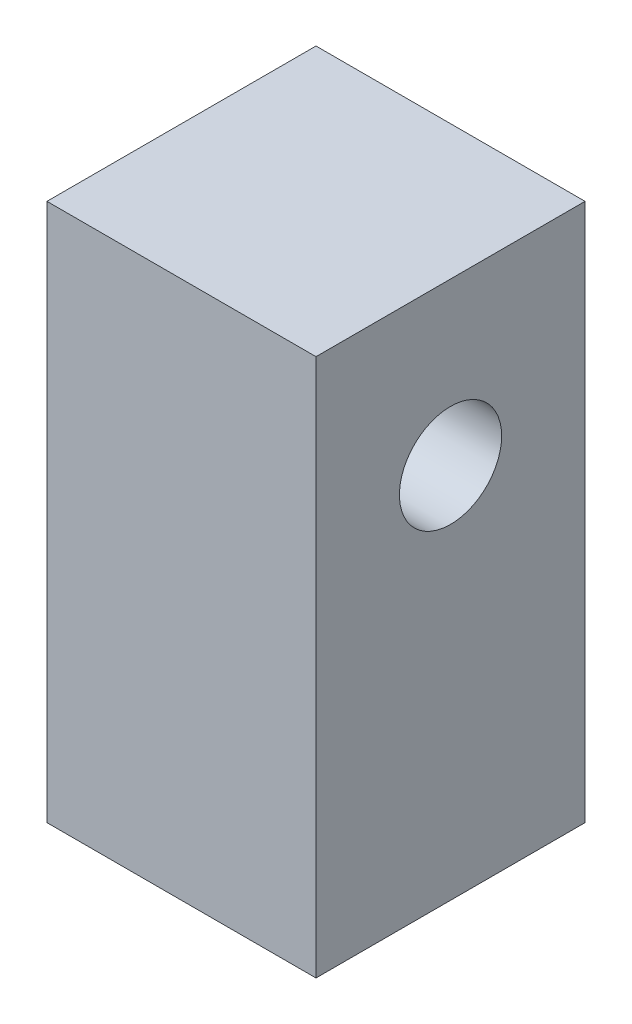
SolidWorks part; units mm, degrees
material "6061 Alloy"
ref_plane "Front Plane" through (0, 0, 0) normal (0, 0, 1) x (1, 0, 0)
ref_plane "Top Plane" through (0, 0, 0) normal (0, 1, 0) x (1, 0, 0)
ref_plane "Right Plane" through (0, 0, 0) normal (1, 0, 0) x (0, 0, -1)
sketch "Croquis1" plane through (0, 0, 0) normal (0, 1, 0) x (1, 0, 0)
  line L1 (6.35, -6.35) -> (-6.35, -6.35)
  line L2 (6.35, -6.35) -> (6.35, 6.35)
  line L3 (6.35, 6.35) -> (-6.35, 6.35)
  line L4 (-6.35, -6.35) -> (-6.35, 6.35)
  line L5 (6.35, -6.35) -> (-6.35, 6.35) construction
  line L6 (6.35, 6.35) -> (-6.35, -6.35) construction
  point P0 (0, 0)
  dimension "D1" = 12.7
  dimension "D2" = 12.7
extrude "Saliente-Extruir1" add sketch "Croquis1" along normal blind 25.4
sketch "Croquis3" plane through (6.35, 0, 0) normal (1, 0, 0) x (0, 0, -1)
  line L0 (0, 0) -> (0, 17.78) construction
  circle A0 centre (0, 17.78) radius 2.413
  dimension "D2" = 4.826
  dimension "D1" = 17.78
extrude "Cortar-Extruir1" cut sketch "Croquis3" against normal blind 25.4
